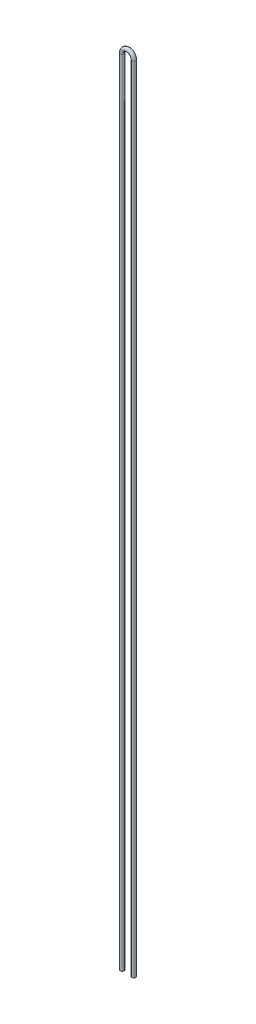
SolidWorks part; units mm, degrees
material "Duranickel(R) 301"
ref_plane "Front Plane" through (0, 0, 0) normal (0, 0, 1) x (1, 0, 0)
ref_plane "Top Plane" through (0, 0, 0) normal (0, 1, 0) x (1, 0, 0)
ref_plane "Right Plane" through (0, 0, 0) normal (1, 0, 0) x (0, 0, -1)
sketch "Sketch1" plane through (0, 0, 0) normal (0, 1, 0) x (1, 0, 0)
  circle A1 centre (0.15, 0) radius 0.05
  dimension "D1" = 0.15
  dimension "D2" = 0.1
sketch "Sketch2" plane through (0, 0, 0) normal (0, 0, 1) x (1, 0, 0)
  line L0 (-0.15, 0) -> (-0.15, 20.5)
  line L2 (0.15, 0) -> (0.15, 20.5)
  line L3 (0.2, 0) -> (0.1, 0) construction
  arc A0 (-0.15, 20.5) -> (0.15, 20.5) centre (0, 20.5) cw
  dimension "D1" = 20.5
  dimension "D2" = 0.3
sweep "Sweep1" add profiles "Sketch1" path "Sketch2"
